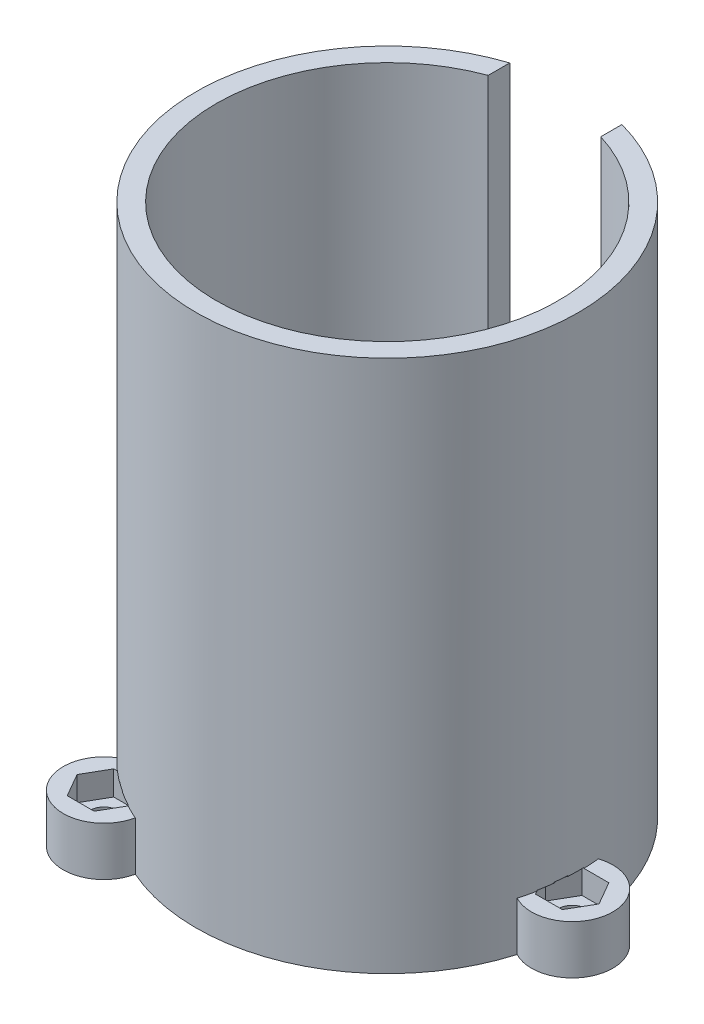
SolidWorks part; units mm, degrees
other "Removable Drive Motor Guard"
ref_plane "Front Plane" through (0, 0, 0) normal (0, 0, 1) x (1, 0, 0)
ref_plane "Top Plane" through (0, 0, 0) normal (0, 1, 0) x (1, 0, 0)
ref_plane "Right Plane" through (0, 0, 0) normal (1, 0, 0) x (0, 0, -1)
sketch3d "Wheel support rails 1 profile datum points"
  point P0 (-56.2917, -200, 0)
  point P1 (-46.2917, -200, 0)
  point P2 (-56.2917, -200, -10)
ref_plane "Wheel support rails 1 profile plane" through (0, -200, 0) normal (0, 1, 0) x (1, 0, 0)
sketch "Wheel support rails 1 profile" plane through (0, -200, 0) normal (0, 1, 0) x (1, 0, 0)
  line L0 (-19.3635, 72.5518) -> (-19.796, 72.5518)
  line L1 (-6.3465, 75.9224) -> (-6.3465, 73.3203)
  line L2 (-24.2184, 74.6449) -> (-27.9139, 74.6449)
  line L3 (-22.4092, 80.8581) -> (-22.4092, 77.4669)
  line L4 (-18.2872, 77.3449) -> (-19.796, 77.3449)
  line L5 (-19.796, 77.3449) -> (-19.796, 72.5518)
  arc A0 (-23.7947, 70.9547) -> (-19.3635, 72.5518) centre (-23.0746, 75.9026) ccw
  arc A1 (-23.7947, 70.9547) -> (-26.6985, 37.7638) centre (-12.5092, 53.2449) ccw
  circle A2 centre (12.3957, 51.066) radius 1.7
  circle A3 centre (-26.8486, 32.7661) radius 1.7
  arc A4 (-22.2036, 34.6164) -> (-26.6985, 37.7638) centre (-26.8486, 32.7661) ccw
  arc A5 (-22.2036, 34.6164) -> (7.9925, 48.6971) centre (-12.5092, 53.2449) ccw
  arc A6 (8.4707, 54.1635) -> (7.9925, 48.6971) centre (12.3957, 51.066) ccw
  arc A7 (8.4707, 54.1635) -> (-6.3465, 73.3203) centre (-12.5092, 53.2449) ccw
  arc A8 (10.8492, 55.8208) -> (-6.3465, 75.9224) centre (-12.5092, 53.2449) ccw
  arc A9 (10.047, 46.6519) -> (10.8492, 55.8208) centre (12.3957, 51.066) ccw
  arc A10 (-21.9576, 31.728) -> (10.047, 46.6519) centre (-12.5092, 53.2449) ccw
  arc A11 (-29.497, 37.0071) -> (-21.9576, 31.728) centre (-26.8486, 32.7661) ccw
  arc A12 (-26.4192, 72.1859) -> (-29.497, 37.0071) centre (-12.5092, 53.2449) ccw
  arc A13 (-27.9139, 74.6449) -> (-26.4192, 72.1859) centre (-23.0746, 75.9026) ccw
  arc A14 (-24.2184, 74.6449) -> (-22.4092, 77.4669) centre (-23.0746, 75.9026) ccw
  arc A15 (-18.2872, 77.3449) -> (-22.4092, 80.8581) centre (-23.0746, 75.9026) ccw
extrude "Wheel support rails 1 extrusion" add sketch "Wheel support rails 1 profile" along normal blind 3 separate body
sketch3d "Wheel support rails 2 profile datum points"
  point P0 (-56.2917, -197, 0)
  point P1 (-46.2917, -197, 0)
  point P2 (-56.2917, -197, -10)
ref_plane "Wheel support rails 2 profile plane" through (0, -197, 0) normal (0, 1, 0) x (1, 0, 0)
sketch "Wheel support rails 2 profile" plane through (0, -197, 0) normal (0, 1, 0) x (1, 0, 0)
  line L0 (-19.3635, 72.5518) -> (-19.796, 72.5518)
  line L1 (9.0957, 51.066) -> (10.7457, 53.9239)
  line L2 (10.7457, 48.2081) -> (9.0957, 51.066)
  line L3 (10.7457, 53.9239) -> (14.0457, 53.9239)
  line L4 (14.0457, 48.2081) -> (10.7457, 48.2081)
  line L5 (14.0457, 53.9239) -> (15.6957, 51.066)
  line L6 (15.6957, 51.066) -> (14.0457, 48.2081)
  line L7 (-30.1486, 32.7661) -> (-28.4986, 35.624)
  line L8 (-28.4986, 29.9082) -> (-30.1486, 32.7661)
  line L9 (-28.4986, 35.624) -> (-25.1986, 35.624)
  line L10 (-25.1986, 29.9082) -> (-28.4986, 29.9082)
  line L11 (-25.1986, 35.624) -> (-23.5486, 32.7661)
  line L12 (-23.5486, 32.7661) -> (-25.1986, 29.9082)
  line L13 (-6.3465, 75.9224) -> (-6.3465, 73.3203)
  line L14 (-24.7246, 73.0447) -> (-25.6485, 74.6449)
  line L15 (-21.4246, 73.0447) -> (-24.7246, 73.0447)
  line L16 (-25.6485, 74.6449) -> (-27.9139, 74.6449)
  line L17 (-19.796, 75.8655) -> (-21.4246, 73.0447)
  line L18 (-22.4092, 78.7605) -> (-21.4246, 78.7605)
  line L19 (-22.4092, 80.8581) -> (-22.4092, 78.7605)
  line L20 (-21.4246, 78.7605) -> (-19.796, 75.9396)
  line L21 (-19.796, 77.3449) -> (-19.796, 75.9396)
  line L22 (-19.796, 75.8655) -> (-19.796, 72.5518)
  line L23 (-18.2872, 77.3449) -> (-19.796, 77.3449)
  arc A0 (-23.7947, 70.9547) -> (-19.3635, 72.5518) centre (-23.0746, 75.9026) ccw
  arc A1 (-23.7947, 70.9547) -> (-26.6985, 37.7638) centre (-12.5092, 53.2449) ccw
  arc A2 (-22.2036, 34.6164) -> (-26.6985, 37.7638) centre (-26.8486, 32.7661) ccw
  arc A3 (-22.2036, 34.6164) -> (7.9925, 48.6971) centre (-12.5092, 53.2449) ccw
  arc A4 (8.4707, 54.1635) -> (7.9925, 48.6971) centre (12.3957, 51.066) ccw
  arc A5 (8.4707, 54.1635) -> (-6.3465, 73.3203) centre (-12.5092, 53.2449) ccw
  arc A6 (10.8492, 55.8208) -> (-6.3465, 75.9224) centre (-12.5092, 53.2449) ccw
  arc A7 (10.047, 46.6519) -> (10.8492, 55.8208) centre (12.3957, 51.066) ccw
  arc A8 (-21.9576, 31.728) -> (10.047, 46.6519) centre (-12.5092, 53.2449) ccw
  arc A9 (-29.497, 37.0071) -> (-21.9576, 31.728) centre (-26.8486, 32.7661) ccw
  arc A10 (-26.4192, 72.1859) -> (-29.497, 37.0071) centre (-12.5092, 53.2449) ccw
  arc A11 (-27.9139, 74.6449) -> (-26.4192, 72.1859) centre (-23.0746, 75.9026) ccw
  arc A12 (-18.2872, 77.3449) -> (-22.4092, 80.8581) centre (-23.0746, 75.9026) ccw
extrude "Wheel support rails 2 extrusion" add sketch "Wheel support rails 2 profile" along normal blind 3
sketch3d "Wheel support rails 3 profile datum points"
  point P0 (-56.2917, -194, 0)
  point P1 (-46.2917, -194, 0)
  point P2 (-56.2917, -194, -10)
ref_plane "Wheel support rails 3 profile plane" through (0, -194, 0) normal (0, 1, 0) x (1, 0, 0)
sketch "Wheel support rails 3 profile" plane through (0, -194, 0) normal (0, 1, 0) x (1, 0, 0)
  line L0 (9.0957, 51.066) -> (10.7457, 53.9239)
  line L1 (10.5252, 48.59) -> (9.0957, 51.066)
  line L2 (10.7457, 53.9239) -> (10.981, 53.9239)
  line L3 (-28.0576, 35.624) -> (-25.1986, 35.624)
  line L4 (-25.1986, 35.624) -> (-23.5486, 32.7661)
  line L5 (-23.5486, 32.7661) -> (-23.6663, 32.5623)
  line L6 (-6.3465, 75.9224) -> (-6.3465, 73.3203)
  line L7 (-19.796, 75.5866) -> (-19.796, 72.9401)
  line L8 (-19.9951, 75.5207) -> (-21.4246, 73.0447)
  line L9 (-24.7246, 73.0447) -> (-24.8423, 73.2485)
  line L10 (-21.4246, 73.0447) -> (-24.7246, 73.0447)
  arc A0 (-23.6663, 32.5623) -> (10.5252, 48.59) centre (-12.5092, 53.2449) ccw
  arc A1 (10.981, 53.9239) -> (-6.3465, 75.9224) centre (-12.5092, 53.2449) ccw
  arc A2 (-24.8423, 73.2485) -> (-28.0576, 35.624) centre (-12.5092, 53.2449) ccw
  arc A3 (-19.796, 72.9401) -> (-6.3465, 73.3203) centre (-12.5092, 53.2449) ccw
  arc A4 (-19.796, 75.5866) -> (-19.9951, 75.5207) centre (-12.5092, 53.2449) ccw
extrude "Wheel support rails 3 extrusion" add sketch "Wheel support rails 3 profile" along normal blind 0.1
sketch3d "Wheel support rails 4 profile datum points"
  point P0 (-56.2917, -193.9, 0)
  point P1 (-46.2917, -193.9, 0)
  point P2 (-56.2917, -193.9, -10)
ref_plane "Wheel support rails 4 profile plane" through (0, -193.9, 0) normal (0, 1, 0) x (1, 0, 0)
sketch "Wheel support rails 4 profile" plane through (0, -193.9, 0) normal (0, 1, 0) x (1, 0, 0)
  line L0 (-6.3465, 75.9224) -> (-6.3465, 73.3203)
  line L1 (-19.796, 75.5866) -> (-19.796, 72.9401)
  arc A0 (10.9562, 51.9704) -> (10.821, 50.4253) centre (12.3957, 51.066) ccw
  arc A1 (10.9562, 51.9704) -> (-6.3465, 75.9224) centre (-12.5092, 53.2449) ccw
  arc A2 (-25.3456, 33.5605) -> (10.821, 50.4253) centre (-12.5092, 53.2449) ccw
  arc A3 (-25.3456, 33.5605) -> (-26.6162, 34.4501) centre (-26.8486, 32.7661) ccw
  arc A4 (-23.1382, 74.2038) -> (-26.6162, 34.4501) centre (-12.5092, 53.2449) ccw
  arc A5 (-19.796, 72.9401) -> (-6.3465, 73.3203) centre (-12.5092, 53.2449) ccw
  arc A6 (-19.796, 75.5866) -> (-21.7324, 74.8593) centre (-12.5092, 53.2449) ccw
  arc A7 (-23.1382, 74.2038) -> (-21.7324, 74.8593) centre (-23.0746, 75.9026) ccw
extrude "Wheel support rails 4 extrusion" add sketch "Wheel support rails 4 profile" along normal blind 0.1
sketch3d "Pivot backing 5 profile datum points"
  point P0 (-56.2917, -193.8, 0)
  point P1 (-46.2917, -193.8, 0)
  point P2 (-56.2917, -193.8, -10)
ref_plane "Pivot backing 5 profile plane" through (0, -193.8, 0) normal (0, 1, 0) x (1, 0, 0)
sketch "Pivot backing 5 profile" plane through (0, -193.8, 0) normal (0, 1, 0) x (1, 0, 0)
  line L0 (-6.3465, 75.9224) -> (-6.3465, 73.3203)
  line L1 (-19.796, 75.5866) -> (-19.796, 72.9401)
  arc A0 (-19.796, 75.5866) -> (-6.3465, 75.9224) centre (-12.5092, 53.2449) ccw
  arc A1 (-19.796, 72.9401) -> (-6.3465, 73.3203) centre (-12.5092, 53.2449) ccw
extrude "Pivot backing 5 extrusion" add sketch "Pivot backing 5 profile" along normal blind 59.3
